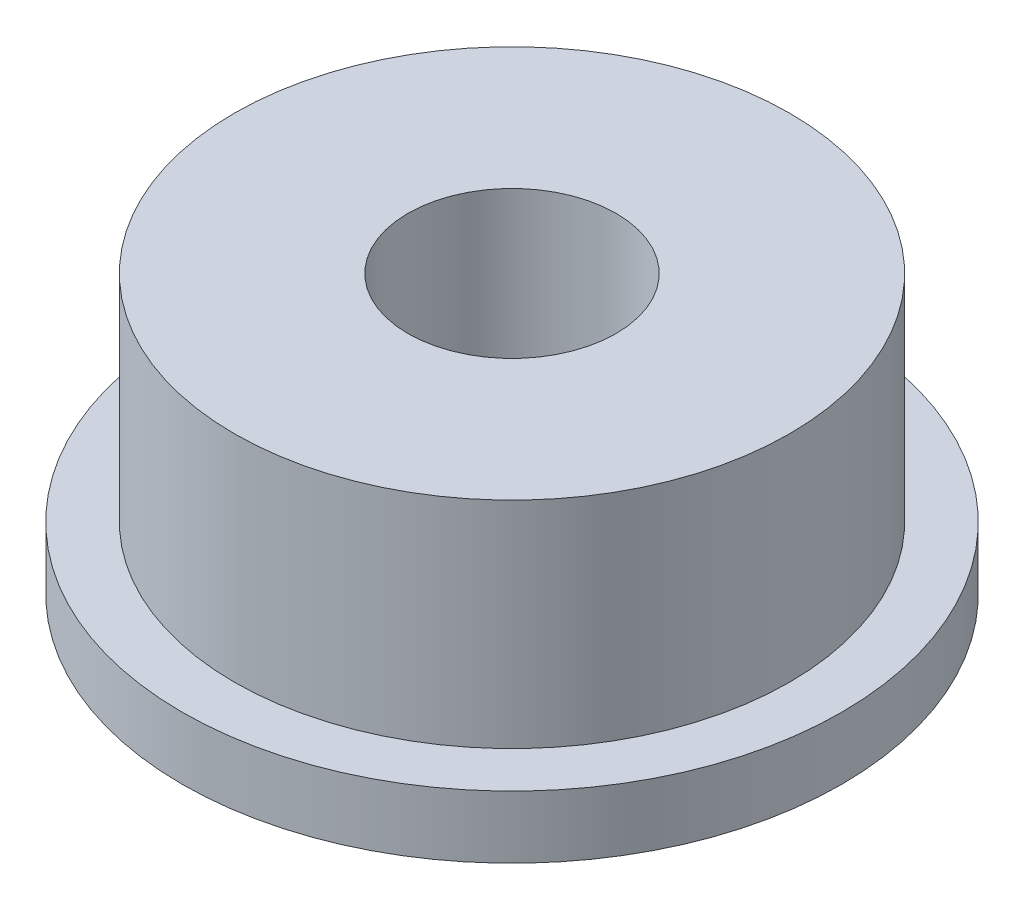
SolidWorks part; units mm, degrees
material "Chrome Stainless Steel"
ref_plane "Front Plane" through (0, 0, 0) normal (0, 0, 1) x (1, 0, 0)
ref_plane "Top Plane" through (0, 0, 0) normal (0, 1, 0) x (1, 0, 0)
ref_plane "Right Plane" through (0, 0, 0) normal (1, 0, 0) x (0, 0, -1)
sketch "Sketch1" plane through (0, 0, 0) normal (0, 0, 1) x (1, 0, 0)
  line L0 (1.5, 0) -> (4.75, 0)
  line L1 (4.75, 0) -> (4.75, 0.9)
  line L2 (4.75, 0.9) -> (4, 0.9)
  line L3 (4, 0.9) -> (4, 4)
  line L4 (4, 4) -> (1.5, 4)
  line L5 (1.5, 0) -> (1.5, 4) construction
  line L6 (0, 4) -> (0, 0) construction
  line L7 (1.5, 0) -> (1.5, 4)
  dimension "D1" = 1.5
  dimension "D2" = 4.75
  dimension "D3" = 0.9
  dimension "D4" = 4
  dimension "D5" = 4
revolve "Revolve1" add sketch "Sketch1" angle 360 about L6
